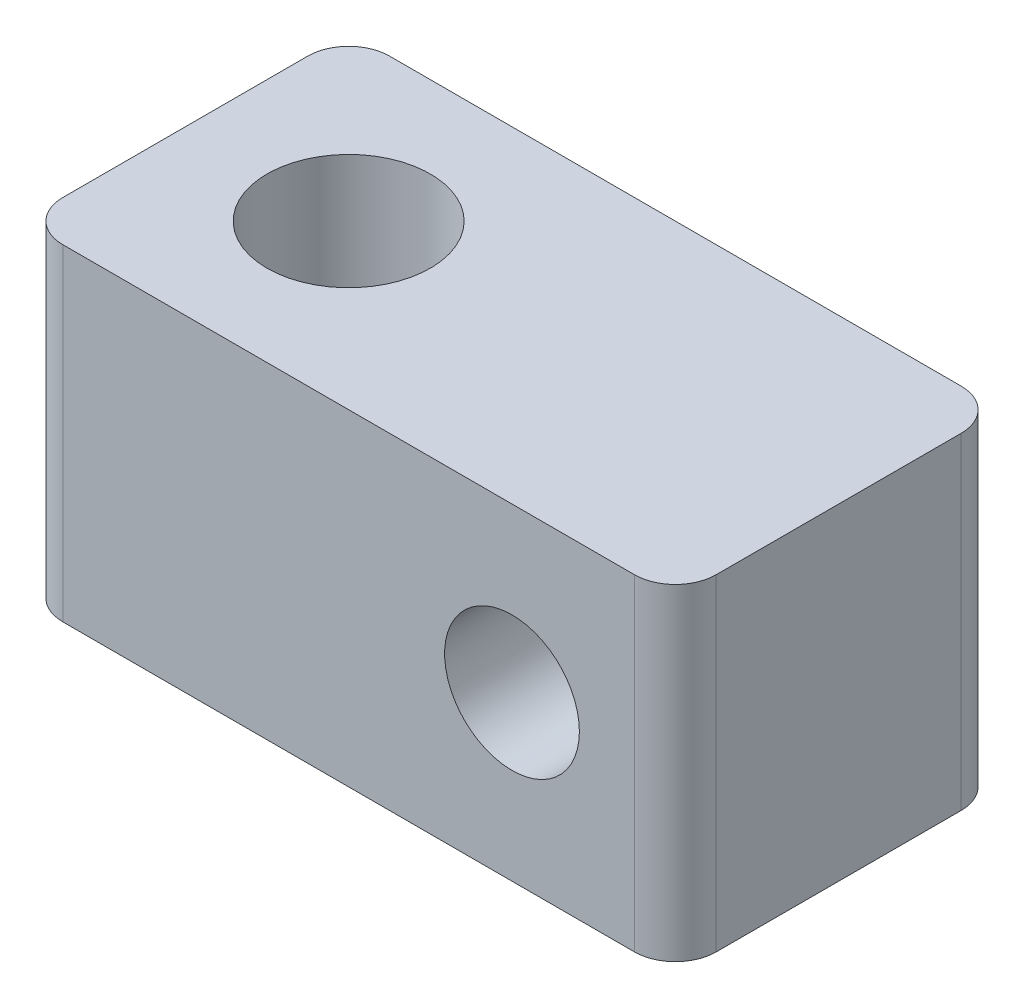
SolidWorks part; units mm, degrees
material "6061 合金"
ref_plane "前视基准面" through (0, 0, 0) normal (0, 0, 1) x (1, 0, 0)
ref_plane "上视基准面" through (0, 0, 0) normal (0, 1, 0) x (1, 0, 0)
ref_plane "右视基准面" through (0, 0, 0) normal (1, 0, 0) x (0, 0, -1)
other "Configuration Table"
sketch "草图1" plane through (0, 0, 0) normal (0, 1, 0) x (1, 0, 0)
  line L1 (-8, 4) -> (8, 4)
  line L2 (-8, 4) -> (-8, -4)
  line L3 (-8, -4) -> (8, -4)
  line L4 (8, 4) -> (8, -4)
  line L5 (-8, 4) -> (8, -4) construction
  line L6 (-8, -4) -> (8, 4) construction
  point P0 (0, 0)
  dimension "D1" = 8
  dimension "D2" = 16
extrude "凸台-拉伸1" add sketch "草图1" along normal blind 8
hole_wizard "M4 螺纹孔2" positions "草图5" profile "草图6" tap size "M4" standard "GB"
sketch "草图5" plane through (0, 0, 4) normal (0, 0, 1) x (1, 0, 0)
  line L0 (8, 8) -> (8, 0) construction
  line L1 (-8, 0) -> (8, 0) construction
  point P0 (4, 4)
  dimension "D1" = 4
  dimension "D2" = 4
sketch "草图6" plane through (4, 4, 4) normal (1, 0, 0) x (0, -1, 0)
  line L0 (0, 0) -> (0, 12.5914)
  line L1 (0, 12.5914) -> (1.65, 11.6)
  line L2 (1.65, 11.6) -> (1.65, 0)
  line L5 (1.65, 0) -> (0, 0)
  line L10 (0, 12.5914) -> (-1.65, 11.6) construction
  line L11 (0, -6.35) -> (0, 107.95) construction
  dimension "螺纹孔钻头直径" = 3.3
  dimension "螺纹孔钻头深度" = 11.6
  dimension "导头角度" = 118
cosmetic thread "孔螺蚊线2" parameters "D1"=9.5, "D2"=4
fillet "圆角1" radius 1 4 edges at (8, 4, 4) (-8, 4, -4) (8, 4, -4) (-8, 4, 4)
sketch "草图7" plane through (0, 8, 0) normal (0, 1, 0) x (1, 0, 0)
  line L0 (-8, 3) -> (-8, -3) construction
  circle A0 centre (-4, 0) radius 2
  dimension "D1" = 4
  dimension "D2" = 4
extrude "切除-拉伸1" cut sketch "草图7" against normal blind 10
